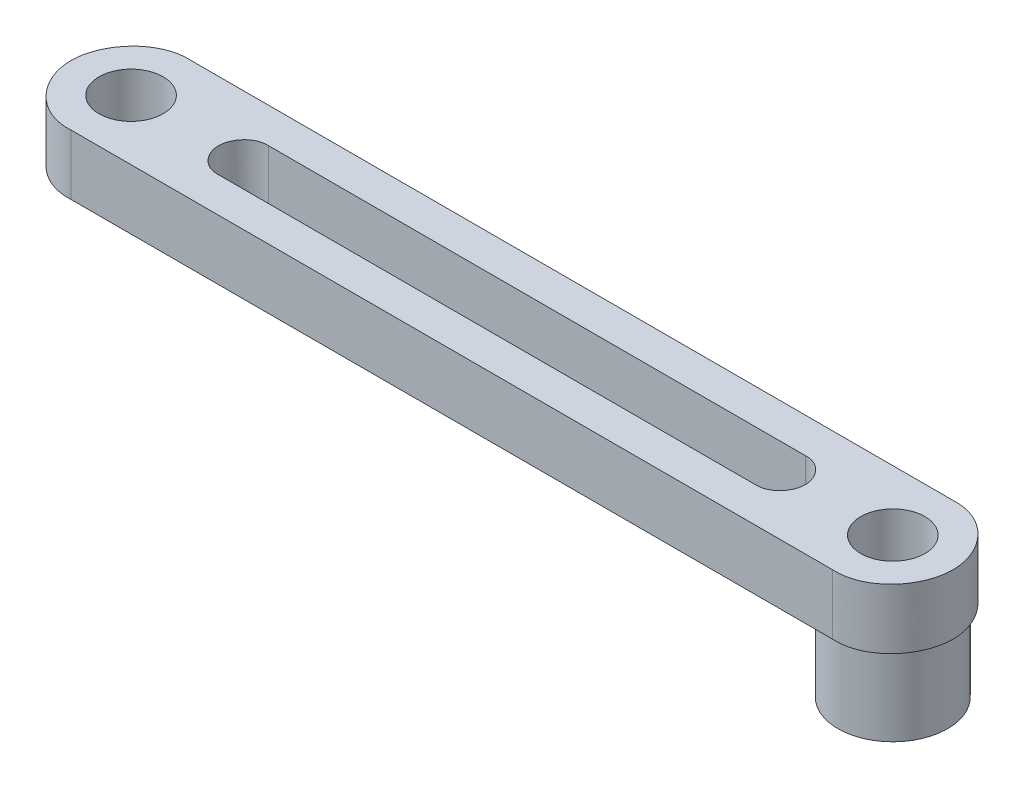
SolidWorks part; units mm, degrees
ref_plane "Plan de face" through (0, 0, 0) normal (0, 0, 1) x (1, 0, 0)
ref_plane "Plan de dessus" through (0, 0, 0) normal (0, 1, 0) x (1, 0, 0)
ref_plane "Plan de droite" through (0, 0, 0) normal (1, 0, 0) x (0, 0, -1)
sketch "Esquisse1" plane through (0, 0, 0) normal (0, 1, 0) x (1, 0, 0)
  line L0 (-55, 0) -> (55, 0) construction
  line L1 (0, -55) -> (0, 55) construction
  line L2 (-19, 3) -> (19, 3)
  line L3 (-19, -3) -> (19, -3)
  circle A0 centre (-19, 0) radius 1.6
  circle A1 centre (-19, 0) radius 3 construction
  circle A2 centre (19, 0) radius 3 construction
  circle A3 centre (19, 0) radius 1.6
  spline S0 degree 3 poles (-19, 3) (-20.6611, 3.1025) (-23.3416, 0.0016) (-20.6556, -3.1058) (-19, -3) knots 0 0 0 0 0.499995 1 1 1 1
  spline S1 degree 3 poles (19, 3) (20.6864, 3.0946) (23.3156, 0.0008) (20.6824, -3.0976) (19, -3) knots 0 0 0 0 0.499942 1 1 1 1
  dimension "D1" = 3.2
  dimension "D2" = 6
  dimension "D3" = 38
extrude "Boss.-Extru.1" add sketch "Esquisse1" along normal blind 3
sketch "Esquisse2" plane through (0, 0, 0) normal (0, -1, 0) x (1, 0, 0)
  circle A0 centre (19, 0) radius 1.6
  circle A1 centre (19, 0) radius 2.7347
  dimension "D1" = 3.2
extrude "Boss.-Extru.2" add sketch "Esquisse2" along normal blind 4
sketch "Esquisse3" plane through (0, 3, 0) normal (0, 1, 0) x (1, 0, 0)
  line L0 (-3.3, 0) -> (3.3, 0) construction
  line L1 (0, -3.3) -> (0, 3.3) construction
  line L2 (13.3904, -1.25) -> (-13.3904, -1.25)
  line L3 (13.3904, 1.25) -> (-13.3904, 1.25)
  circle A0 centre (13.3904, 0) radius 1.25 construction
  circle A1 centre (-13.3904, 0) radius 1.25 construction
  spline S0 degree 3 poles (13.3904, -1.25) (14.0849, -1.2884) (15.2055, -0.0066) (14.0657, 1.2986) (13.3904, 1.25) knots 0 0 0 0 0.500292 1 1 1 1
  spline S1 degree 3 poles (-13.3904, -1.25) (-14.091, -1.2906) (-15.1895, 0.0001) (-14.0916, 1.2901) (-13.3904, 1.25) knots 0 0 0 0 0.500019 1 1 1 1
  dimension "D1" = 2.5
extrude "Enlèv. mat.-Extru.1" cut sketch "Esquisse3" against normal blind 3
